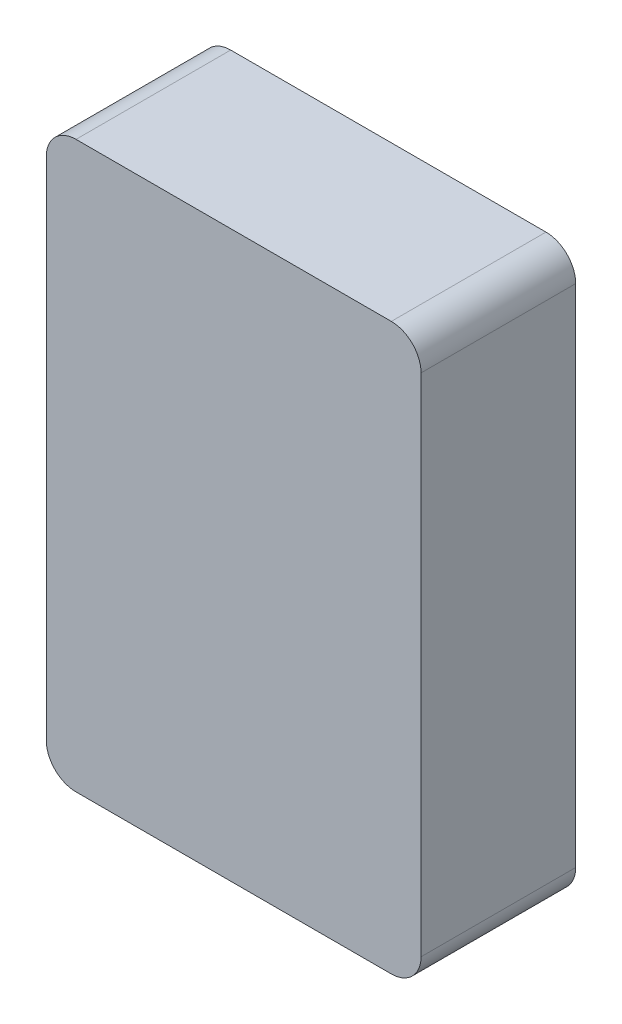
SolidWorks part; units mm, degrees
material "Acrílico (médio-alto impacto)"
ref_plane "Plano frontal" through (0, 0, 0) normal (0, 0, 1) x (1, 0, 0)
ref_plane "Plano superior" through (0, 0, 0) normal (0, 1, 0) x (1, 0, 0)
ref_plane "Plano direito" through (0, 0, 0) normal (1, 0, 0) x (0, 0, -1)
sketch "Esboço3" plane through (0, 0, 0) normal (0, 0, 1) x (1, 0, 0)
  line L0 (0, -34.5217) -> (0, 214.9486) construction
  line L1 (112.8151, 73.9178) -> (-95.5787, 73.9178) construction
  line L6 (-31.5, 26.4178) -> (31.5, 26.4178)
  line L7 (-31.5, 26.4178) -> (-31.5, 121.4178)
  line L8 (-31.5, 121.4178) -> (31.5, 121.4178)
  line L9 (31.5, 26.4178) -> (31.5, 121.4178)
  line L10 (-31.5, 26.4178) -> (31.5, 121.4178) construction
  line L11 (-31.5, 121.4178) -> (31.5, 26.4178) construction
  point P12 (0, 73.9178)
  dimension "D1" = 95
  dimension "D2" = 63
extrude "Ressalto-extrusão1" add sketch "Esboço3" along normal blind 26
fillet "Filete1" radius 5 4 edges at (-31.5, 26.4178, 13) (-31.5, 121.4178, 13) (31.5, 121.4178, 13) (31.5, 26.4178, 13)
